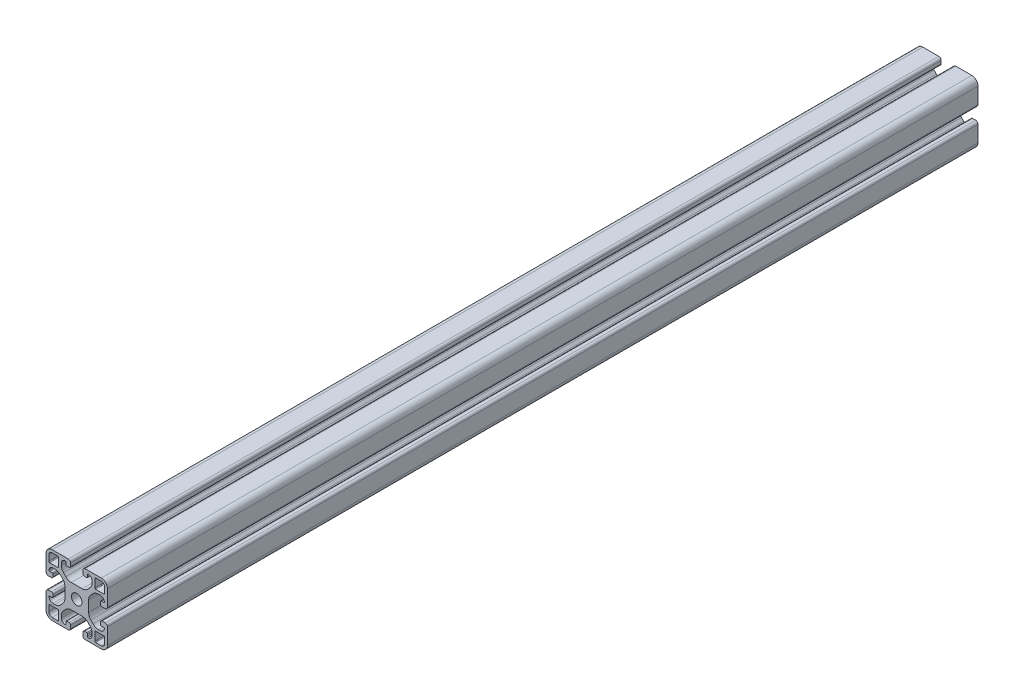
SolidWorks part; units mm, degrees
ref_plane "Plan de face" through (0, 0, 0) normal (0, 0, 1) x (1, 0, 0)
ref_plane "Plan de dessus" through (0, 0, 0) normal (0, 1, 0) x (1, 0, 0)
ref_plane "Plan de droite" through (0, 0, 0) normal (1, 0, 0) x (0, 0, -1)
ref_plane "Plan1" through (0, 0, -30) normal (0, 0, -1) x (-1, 0, 0)
sketch "Esquisse1" plane through (0, 0, -30) normal (0, 0, -1) x (-1, 0, 0)
  line L0 (-4.5, 15) -> (-4.5, 13.5)
  line L1 (-4, 13) -> (-2.5, 13)
  line L2 (-4.5, 10) -> (-5.8076, 10)
  line L3 (-9.3431, 11.4645) -> (-10.7855, 12.9069)
  line L4 (-12.25, 16.4424) -> (-12.25, 23.5576)
  line L5 (-10.7855, 27.0931) -> (-9.3431, 28.5355)
  line L6 (-5.8076, 30) -> (-4.5, 30)
  line L7 (-2.5, 27) -> (-4, 27)
  line L8 (-4.5, 26.5) -> (-4.5, 25)
  line L9 (-3.5, 24) -> (-1.5, 24)
  line L10 (0, 25.5) -> (0, 36)
  line L11 (-4, 40) -> (-14.5, 40)
  line L12 (-16, 38.5) -> (-16, 36.5)
  line L13 (-15, 35.5) -> (-13.5, 35.5)
  line L14 (-13, 36) -> (-13, 37.5)
  line L15 (-10, 35.5) -> (-10, 34.1924)
  line L16 (-11.4645, 30.6569) -> (-12.9069, 29.2145)
  line L17 (-16.4424, 27.75) -> (-23.5576, 27.75)
  line L18 (-27.0931, 29.2145) -> (-28.5355, 30.6569)
  line L19 (-30, 34.1924) -> (-30, 35.5)
  line L20 (-27, 37.5) -> (-27, 36)
  line L21 (-26.5, 35.5) -> (-25, 35.5)
  line L22 (-24, 36.5) -> (-24, 38.5)
  line L23 (-25.5, 40) -> (-36, 40)
  line L24 (-40, 36) -> (-40, 25.5)
  line L25 (-38.5, 24) -> (-36.5, 24)
  line L26 (-35.5, 25) -> (-35.5, 26.5)
  line L27 (-36, 27) -> (-37.5, 27)
  line L28 (-35.5, 30) -> (-34.1924, 30)
  line L29 (-30.6569, 28.5355) -> (-29.2145, 27.0931)
  line L30 (-27.75, 23.5576) -> (-27.75, 16.4424)
  line L31 (-29.2145, 12.9069) -> (-30.6569, 11.4645)
  line L32 (-34.1924, 10) -> (-35.5, 10)
  line L33 (-37.5, 13) -> (-36, 13)
  line L34 (-35.5, 13.5) -> (-35.5, 15)
  line L35 (-36.5, 16) -> (-38.5, 16)
  line L36 (-40, 14.5) -> (-40, 4)
  line L37 (-36, 0) -> (-25.5, 0)
  line L38 (-24, 1.5) -> (-24, 3.5)
  line L39 (-25, 4.5) -> (-26.5, 4.5)
  line L40 (-27, 4) -> (-27, 2.5)
  line L41 (-30, 4.5) -> (-30, 5.8076)
  line L42 (-28.5355, 9.3431) -> (-27.0931, 10.7855)
  line L43 (-23.5576, 12.25) -> (-16.4424, 12.25)
  line L44 (-12.9069, 10.7855) -> (-11.4645, 9.3431)
  line L45 (-10, 5.8076) -> (-10, 4.5)
  line L46 (-13, 2.5) -> (-13, 4)
  line L47 (-13.5, 4.5) -> (-15, 4.5)
  line L48 (-16, 3.5) -> (-16, 1.5)
  line L49 (-14.5, 0) -> (-4, 0)
  line L50 (0, 4) -> (0, 14.5)
  line L51 (-1.5, 16) -> (-3.5, 16)
  line L52 (-4, 1.8) -> (-7.7, 1.8)
  line L53 (-8.2, 2.3) -> (-8.2, 7.7)
  line L54 (-7.7, 8.2) -> (-2.3, 8.2)
  line L55 (-1.8, 7.7) -> (-1.8, 4)
  line L56 (-38.2, 4) -> (-38.2, 7.7)
  line L57 (-37.7, 8.2) -> (-32.3, 8.2)
  line L58 (-31.8, 7.7) -> (-31.8, 2.3)
  line L59 (-32.3, 1.8) -> (-36, 1.8)
  line L60 (-36, 38.2) -> (-32.3, 38.2)
  line L61 (-31.8, 37.7) -> (-31.8, 32.3)
  line L62 (-32.3, 31.8) -> (-37.7, 31.8)
  line L63 (-38.2, 32.3) -> (-38.2, 36)
  line L64 (-1.8, 36) -> (-1.8, 32.3)
  line L65 (-2.3, 31.8) -> (-7.7, 31.8)
  line L66 (-8.2, 32.3) -> (-8.2, 37.7)
  line L67 (-7.7, 38.2) -> (-4, 38.2)
  arc A0 (-4.5, 13.5) -> (-4, 13) centre (-4, 13.5) ccw
  arc A1 (-2.5, 13) -> (-2, 12.5) centre (-2.5, 12.5) cw
  arc A2 (-2, 12.5) -> (-4.5, 10) centre (-4.5, 12.5) cw
  arc A3 (-5.8076, 10) -> (-9.3431, 11.4645) centre (-5.8076, 15) cw
  arc A4 (-10.7855, 12.9069) -> (-12.25, 16.4424) centre (-7.25, 16.4424) cw
  arc A5 (-12.25, 23.5576) -> (-10.7855, 27.0931) centre (-7.25, 23.5576) cw
  arc A6 (-9.3431, 28.5355) -> (-5.8076, 30) centre (-5.8076, 25) cw
  arc A7 (-4.5, 30) -> (-2, 27.5) centre (-4.5, 27.5) cw
  arc A8 (-2, 27.5) -> (-2.5, 27) centre (-2.5, 27.5) cw
  arc A9 (-4, 27) -> (-4.5, 26.5) centre (-4, 26.5) ccw
  arc A10 (-4.5, 25) -> (-3.5, 24) centre (-3.5, 25) ccw
  arc A11 (-1.5, 24) -> (0, 25.5) centre (-1.5, 25.5) ccw
  arc A12 (0, 36) -> (-4, 40) centre (-4, 36) ccw
  arc A13 (-14.5, 40) -> (-16, 38.5) centre (-14.5, 38.5) ccw
  arc A14 (-16, 36.5) -> (-15, 35.5) centre (-15, 36.5) ccw
  arc A15 (-13.5, 35.5) -> (-13, 36) centre (-13.5, 36) ccw
  arc A16 (-13, 37.5) -> (-12.5, 38) centre (-12.5, 37.5) cw
  arc A17 (-12.5, 38) -> (-10, 35.5) centre (-12.5, 35.5) cw
  arc A18 (-10, 34.1924) -> (-11.4645, 30.6569) centre (-15, 34.1924) cw
  arc A19 (-12.9069, 29.2145) -> (-16.4424, 27.75) centre (-16.4424, 32.75) cw
  arc A20 (-23.5576, 27.75) -> (-27.0931, 29.2145) centre (-23.5576, 32.75) cw
  arc A21 (-28.5355, 30.6569) -> (-30, 34.1924) centre (-25, 34.1924) cw
  arc A22 (-30, 35.5) -> (-27.5, 38) centre (-27.5, 35.5) cw
  arc A23 (-27.5, 38) -> (-27, 37.5) centre (-27.5, 37.5) cw
  arc A24 (-27, 36) -> (-26.5, 35.5) centre (-26.5, 36) ccw
  arc A25 (-25, 35.5) -> (-24, 36.5) centre (-25, 36.5) ccw
  arc A26 (-24, 38.5) -> (-25.5, 40) centre (-25.5, 38.5) ccw
  arc A27 (-36, 40) -> (-40, 36) centre (-36, 36) ccw
  arc A28 (-40, 25.5) -> (-38.5, 24) centre (-38.5, 25.5) ccw
  arc A29 (-36.5, 24) -> (-35.5, 25) centre (-36.5, 25) ccw
  arc A30 (-35.5, 26.5) -> (-36, 27) centre (-36, 26.5) ccw
  arc A31 (-37.5, 27) -> (-38, 27.5) centre (-37.5, 27.5) cw
  arc A32 (-38, 27.5) -> (-35.5, 30) centre (-35.5, 27.5) cw
  arc A33 (-34.1924, 30) -> (-30.6569, 28.5355) centre (-34.1924, 25) cw
  arc A34 (-29.2145, 27.0931) -> (-27.75, 23.5576) centre (-32.75, 23.5576) cw
  arc A35 (-27.75, 16.4424) -> (-29.2145, 12.9069) centre (-32.75, 16.4424) cw
  arc A36 (-30.6569, 11.4645) -> (-34.1924, 10) centre (-34.1924, 15) cw
  arc A37 (-35.5, 10) -> (-38, 12.5) centre (-35.5, 12.5) cw
  arc A38 (-38, 12.5) -> (-37.5, 13) centre (-37.5, 12.5) cw
  arc A39 (-36, 13) -> (-35.5, 13.5) centre (-36, 13.5) ccw
  arc A40 (-35.5, 15) -> (-36.5, 16) centre (-36.5, 15) ccw
  arc A41 (-38.5, 16) -> (-40, 14.5) centre (-38.5, 14.5) ccw
  arc A42 (-40, 4) -> (-36, 0) centre (-36, 4) ccw
  arc A43 (-25.5, 0) -> (-24, 1.5) centre (-25.5, 1.5) ccw
  arc A44 (-24, 3.5) -> (-25, 4.5) centre (-25, 3.5) ccw
  arc A45 (-26.5, 4.5) -> (-27, 4) centre (-26.5, 4) ccw
  arc A46 (-27, 2.5) -> (-27.5, 2) centre (-27.5, 2.5) cw
  arc A47 (-27.5, 2) -> (-30, 4.5) centre (-27.5, 4.5) cw
  arc A48 (-30, 5.8076) -> (-28.5355, 9.3431) centre (-25, 5.8076) cw
  arc A49 (-27.0931, 10.7855) -> (-23.5576, 12.25) centre (-23.5576, 7.25) cw
  arc A50 (-16.4424, 12.25) -> (-12.9069, 10.7855) centre (-16.4424, 7.25) cw
  arc A51 (-11.4645, 9.3431) -> (-10, 5.8076) centre (-15, 5.8076) cw
  arc A52 (-10, 4.5) -> (-12.5, 2) centre (-12.5, 4.5) cw
  arc A53 (-12.5, 2) -> (-13, 2.5) centre (-12.5, 2.5) cw
  arc A54 (-13, 4) -> (-13.5, 4.5) centre (-13.5, 4) ccw
  arc A55 (-15, 4.5) -> (-16, 3.5) centre (-15, 3.5) ccw
  arc A56 (-16, 1.5) -> (-14.5, 0) centre (-14.5, 1.5) ccw
  arc A57 (-4, 0) -> (0, 4) centre (-4, 4) ccw
  arc A58 (0, 14.5) -> (-1.5, 16) centre (-1.5, 14.5) ccw
  arc A59 (-3.5, 16) -> (-4.5, 15) centre (-3.5, 15) ccw
  circle A60 centre (-20, 20) radius 3.4
  arc A61 (-1.8, 4) -> (-4, 1.8) centre (-4, 4) cw
  arc A62 (-7.7, 1.8) -> (-8.2, 2.3) centre (-7.7, 2.3) cw
  arc A63 (-8.2, 7.7) -> (-7.7, 8.2) centre (-7.7, 7.7) cw
  arc A64 (-2.3, 8.2) -> (-1.8, 7.7) centre (-2.3, 7.7) cw
  arc A65 (-36, 1.8) -> (-38.2, 4) centre (-36, 4) cw
  arc A66 (-38.2, 7.7) -> (-37.7, 8.2) centre (-37.7, 7.7) cw
  arc A67 (-32.3, 8.2) -> (-31.8, 7.7) centre (-32.3, 7.7) cw
  arc A68 (-31.8, 2.3) -> (-32.3, 1.8) centre (-32.3, 2.3) cw
  arc A69 (-38.2, 36) -> (-36, 38.2) centre (-36, 36) cw
  arc A70 (-32.3, 38.2) -> (-31.8, 37.7) centre (-32.3, 37.7) cw
  arc A71 (-31.8, 32.3) -> (-32.3, 31.8) centre (-32.3, 32.3) cw
  arc A72 (-37.7, 31.8) -> (-38.2, 32.3) centre (-37.7, 32.3) cw
  arc A73 (-4, 38.2) -> (-1.8, 36) centre (-4, 36) cw
  arc A74 (-1.8, 32.3) -> (-2.3, 31.8) centre (-2.3, 32.3) cw
  arc A75 (-7.7, 31.8) -> (-8.2, 32.3) centre (-7.7, 32.3) cw
  arc A76 (-8.2, 37.7) -> (-7.7, 38.2) centre (-7.7, 37.7) cw
extrude "Boss.-Extru.1" add sketch "Esquisse1" against normal blind 567
